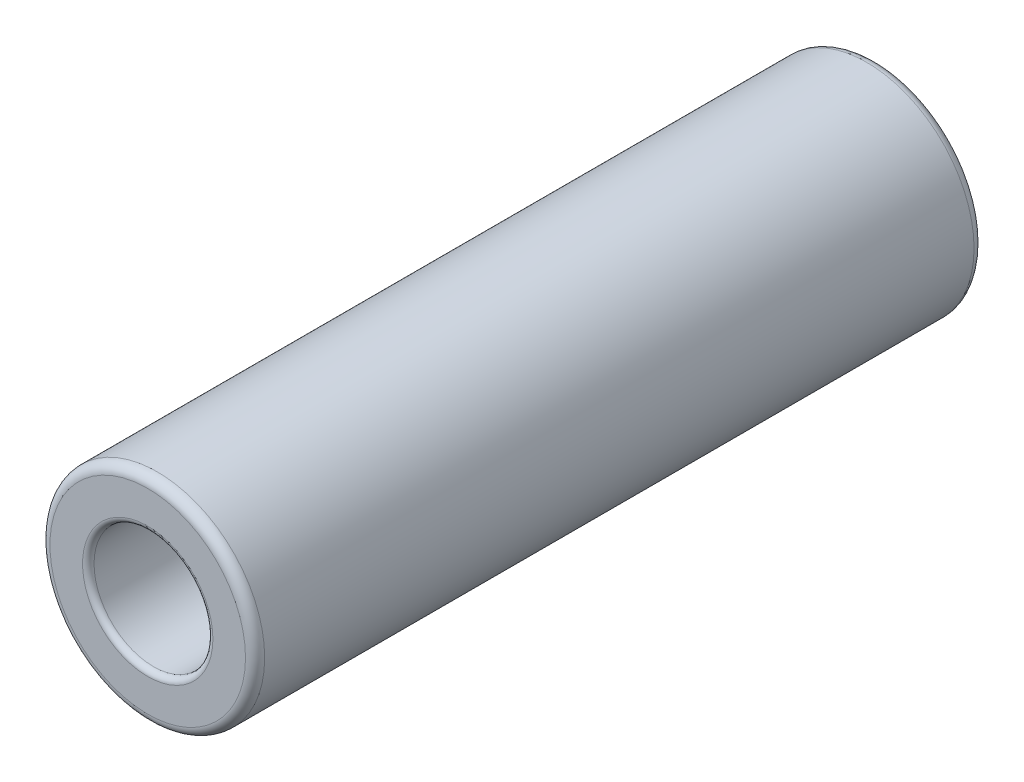
SolidWorks part; units mm, degrees
material "AISI 4340 Steel, annealed"
ref_plane "Front Plane" through (0, 0, 0) normal (0, 0, 1) x (1, 0, 0)
ref_plane "Top Plane" through (0, 0, 0) normal (0, 1, 0) x (1, 0, 0)
ref_plane "Right Plane" through (0, 0, 0) normal (1, 0, 0) x (0, 0, -1)
sketch "Sketch1" plane through (0, 0, 0) normal (0, 0, 1) x (1, 0, 0)
  circle A0 centre (0, 0) radius 14.224
  circle A1 centre (0, 0) radius 7.874
  dimension "D1" = 28.448
  dimension "D2" = 6.35
extrude "Boss-Extrude1" add sketch "Sketch1" along normal blind 96.52
ref_plane "Plane1" through (0, 0, 48.26) normal (0, 0, 1) x (1, 0, 0)
fillet "Fillet1" radius 1.27 2 edges at (14.224, 0, 0) (14.224, 0, 96.52)
fillet "Fillet2" radius 0.762 2 edges at (7.874, 0, 0) (7.874, 0, 96.52)
